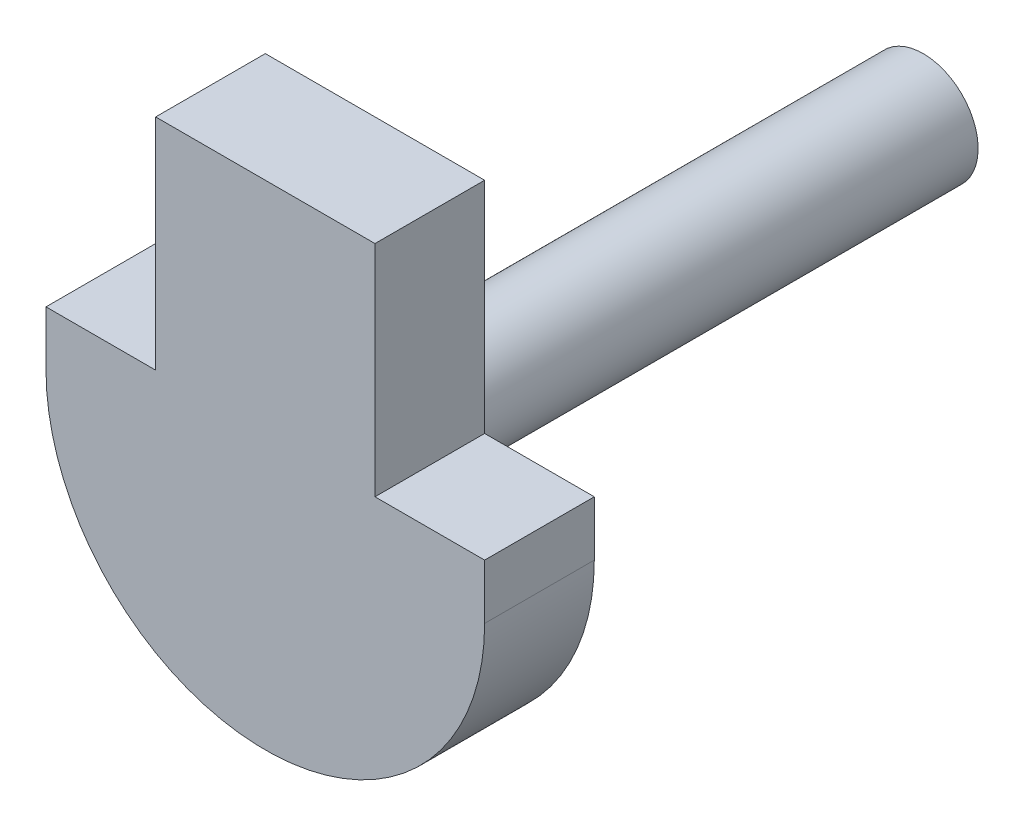
SolidWorks part; units mm, degrees
ref_plane "Plan de face" through (0, 0, 0) normal (0, 0, 1) x (1, 0, 0)
ref_plane "Plan de dessus" through (0, 0, 0) normal (0, 1, 0) x (1, 0, 0)
ref_plane "Plan de droite" through (0, 0, 0) normal (1, 0, 0) x (0, 0, -1)
sketch "Esquisse1" plane through (0, 0, 0) normal (0, 0, 1) x (1, 0, 0)
  line L0 (-20, 0) -> (-20, 5)
  line L2 (20, 5) -> (20, 0)
  line L3 (-20, 5) -> (-10, 5)
  line L4 (-10, 5) -> (-10, 25)
  line L5 (-10, 25) -> (10, 25)
  line L6 (10, 25) -> (10, 5)
  line L7 (10, 5) -> (20, 5)
  arc A0 (-20, 0) -> (20, 0) centre (0, 0) ccw
  point P4 (19.9542, 7.705)
  dimension "D1" = 40
  dimension "D2" = 5
  dimension "D3" = 20
  dimension "D4" = 10
  dimension "D5" = 10
extrude "Boss.-Extru.1" add sketch "Esquisse1" along normal blind 10
sketch "Esquisse2" plane through (0, 0, 0) normal (0, 0, -1) x (-1, 0, 0)
  circle A0 centre (0, 0) radius 5
  dimension "D1" = 10
extrude "Boss.-Extru.2" add sketch "Esquisse2" along normal blind 50
